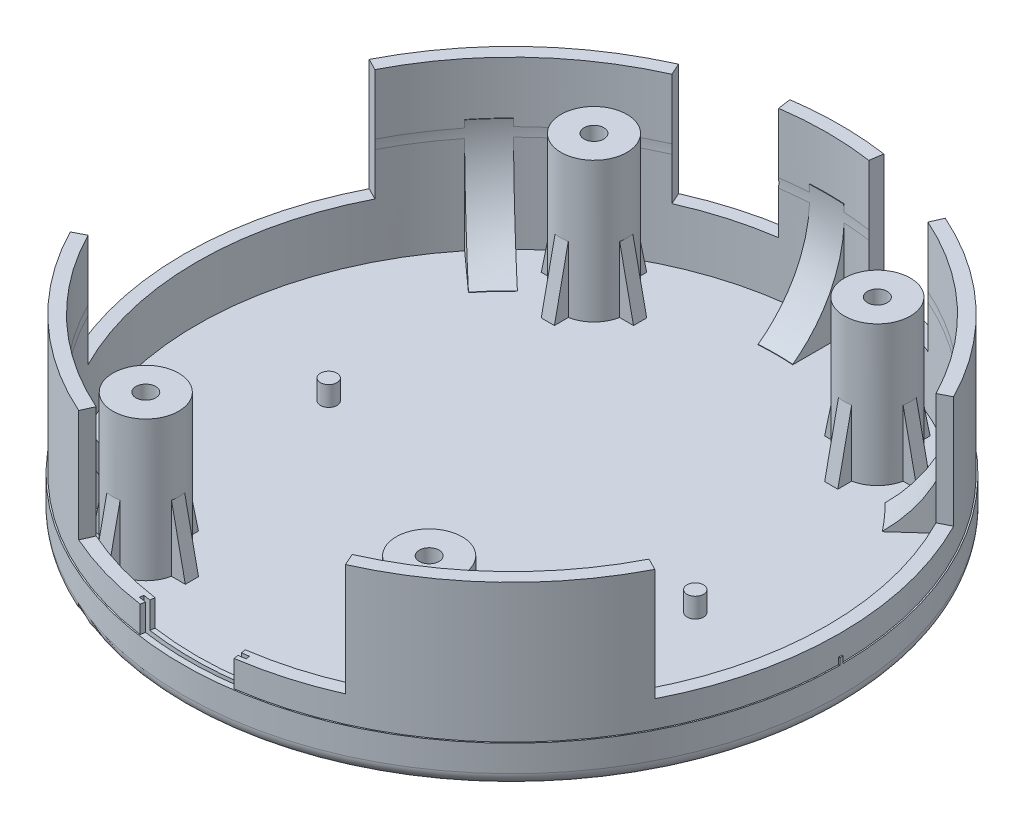
SolidWorks part; units mm, degrees
ref_plane "Front Plane" through (0, 0, 0) normal (0, 0, 1) x (1, 0, 0)
ref_plane "Top Plane" through (0, 0, 0) normal (0, 1, 0) x (1, 0, 0)
ref_plane "Right Plane" through (0, 0, 0) normal (1, 0, 0) x (0, 0, -1)
sketch "Эскиз1" plane through (0, 0, 0) normal (0, 1, 0) x (1, 0, 0)
  circle A0 centre (0, 0) radius 50
  dimension "D1" = 100
extrude "Бобышка-Вытянуть1" add sketch "Эскиз1" along normal blind 6
shell "Оболочка1" thickness 2
sketch "Эскиз3" plane through (0, 2, 0) normal (0, 1, 0) x (1, 0, 0)
  circle A0 centre (0, 0) radius 48 construction
  circle A1 centre (0, 0) radius 48
extrude "Бобышка-Вытянуть2" add sketch "Эскиз3" along normal blind 2
fillet "Скругление1" radius 2 1 edges at (0, 0, 50)
sketch "Эскиз4" plane through (0, 4, 0) normal (0, 1, 0) x (1, 0, 0)
  circle A2 centre (0, 0) radius 47.8
  circle A3 centre (0, 0) radius 49.8
  dimension "D1" = 99.6
  dimension "D2" = 95.6
extrude "Бобышка-Вытянуть3" add sketch "Эскиз4" along normal blind 23
sketch "Эскиз15" plane through (0, 4, 0) normal (0, 1, 0) x (1, 0, 0)
  circle A0 centre (0, 0) radius 50
  circle A1 centre (0, 0) radius 48
  dimension "D1" = 96
  dimension "D2" = 100
extrude "Бобышка-Вытянуть9" add sketch "Эскиз15" along normal blind 2
sketch "Эскиз16" plane through (0, 4, 0) normal (0, 1, 0) x (1, 0, 0)
  line L0 (-37.2524, 30.063) -> (-31.4039, 24.7971)
  line L1 (0, 47.8) -> (2.6705, 47.8) construction
  line L2 (0, 47.8) -> (-2.5855, 47.8) construction
  line L14 (-2.5855, 47.8) -> (-2.5855, 39.9302)
  line L15 (-33.7354, 33.969) -> (-27.8829, 28.6993)
  line L24 (0, 47.8) -> (2.6705, 47.8) construction
  line L25 (2.6705, 47.8) -> (2.6705, 39.9246)
  line L33 (0, 47.8) -> (-2.5855, 47.8) construction
  line L34 (0, 0) -> (0, 14.9931) construction
  line L37 (0, 0) -> (22.7819, 0) construction
  line L38 (0, -47.8) -> (-2.5855, -47.8) construction
  line L41 (33.7354, 33.969) -> (27.8829, 28.6993)
  line L42 (37.2524, 30.063) -> (31.4039, 24.7971)
  line L43 (0, -47.8) -> (2.6705, -47.8) construction
  line L44 (0, -47.8) -> (-2.5855, -47.8) construction
  line L45 (0, -47.8) -> (2.6705, -47.8) construction
  line L46 (37.2524, -30.063) -> (31.4039, -24.7971)
  line L47 (33.7354, -33.969) -> (27.8829, -28.6993)
  line L48 (2.6705, -47.8) -> (2.6705, -39.9246)
  line L49 (-33.7354, -33.969) -> (-27.8829, -28.6993)
  line L50 (-2.5855, -47.8) -> (-2.5855, -39.9302)
  line L51 (-37.2524, -30.063) -> (-31.4039, -24.7971)
  circle A18 centre (0, 0) radius 47.8 construction
  arc A19 (-33.68, 33.919) -> (-37.2004, 30.0162) centre (0, 0) ccw
  arc A20 (-27.8829, 28.6993) -> (-31.4039, 24.7971) centre (0, 0) ccw
  arc A21 (2.6705, 47.7253) -> (-2.5855, 47.73) centre (0, 0) ccw
  arc A22 (2.6705, 39.9246) -> (-2.5855, 39.9302) centre (0, 0) ccw
  arc A23 (33.68, -33.919) -> (37.2004, -30.0162) centre (0, 0) ccw
  arc A24 (27.8829, -28.6993) -> (31.4039, -24.7971) centre (0, 0) ccw
  arc A25 (2.6705, -39.9246) -> (-2.5855, -39.9302) centre (0, 0) cw
  arc A26 (2.6705, -47.7253) -> (-2.5855, -47.73) centre (0, 0) cw
  arc A27 (-27.8829, -28.6993) -> (-31.4039, -24.7971) centre (0, 0) cw
  arc A28 (-33.68, -33.919) -> (-37.2004, -30.0162) centre (0, 0) cw
  arc A29 (27.8829, 28.6993) -> (31.4039, 24.7971) centre (0, 0) cw
  arc A30 (33.68, 33.919) -> (37.2004, 30.0162) centre (0, 0) cw
extrude "Бобышка-Вытянуть10" add sketch "Эскиз16" along normal blind 15
sketch "Эскиз27" plane through (0, 6, 0) normal (0, 1, 0) x (1, 0, 0)
  line L0 (0, 0) -> (-65.748, 0) construction
  line L1 (0, 0) -> (0, 13.4164) construction
  line L14 (49.9994, -0.2541) -> (49.7994, -0.2541)
  line L17 (49.9994, 0.2541) -> (49.7994, 0.2541)
  line L18 (-49.9994, 0.2541) -> (-49.7994, 0.2541)
  line L19 (-49.9994, -0.2541) -> (-49.7994, -0.2541)
  arc A0 (-49.9994, 0.2541) -> (-49.9994, -0.2541) centre (0, 0) ccw
  arc A2 (-49.7994, 0.2541) -> (-49.7994, -0.2541) centre (0, 0) ccw
  arc A13 (49.7994, 0.2541) -> (49.7994, -0.2541) centre (0, 0) cw
  arc A14 (49.9994, 0.2541) -> (49.9994, -0.2541) centre (0, 0) cw
extrude "Бобышка-Вытянуть14" add sketch "Эскиз27" along normal blind 1
sketch "Эскиз28" plane through (0, 4, 0) normal (0, 1, 0) x (1, 0, 0)
  line L0 (-37.2004, 30.0162) -> (-31.4039, 24.7971) construction
  line L2 (-37.2004, 30.0162) -> (-31.4039, 24.7971)
  line L5 (-33.68, 33.919) -> (-27.8829, 28.6993) construction
  line L7 (-33.68, 33.919) -> (-27.8829, 28.6993)
  line L9 (-2.5855, 47.73) -> (-2.5855, 39.9302) construction
  line L11 (-2.5855, 47.73) -> (-2.5855, 39.9302)
  line L14 (2.6705, 47.7253) -> (2.6705, 39.9246) construction
  line L16 (2.6705, 47.7253) -> (2.6705, 39.9246)
  line L19 (33.68, 33.919) -> (27.8829, 28.6993) construction
  line L21 (33.68, 33.919) -> (27.8829, 28.6993)
  line L28 (37.2004, 30.0162) -> (31.4039, 24.7971) construction
  line L30 (37.2004, 30.0162) -> (31.4039, 24.7971)
  line L38 (37.2004, -30.0162) -> (31.4039, -24.7971) construction
  line L39 (37.2004, -30.0162) -> (31.4039, -24.7971)
  line L40 (33.68, -33.919) -> (27.8829, -28.6993) construction
  line L41 (33.68, -33.919) -> (27.8829, -28.6993)
  line L42 (2.6705, -47.7253) -> (2.6705, -39.9246) construction
  line L43 (2.6705, -47.7253) -> (2.6705, -39.9246)
  line L44 (-2.5855, -47.73) -> (-2.5855, -39.9302) construction
  line L45 (-2.5855, -47.73) -> (-2.5855, -39.9302)
  line L46 (-33.68, -33.919) -> (-27.8829, -28.6993) construction
  line L47 (-33.68, -33.919) -> (-27.8829, -28.6993)
  line L48 (-37.2004, -30.0162) -> (-31.4039, -24.7971) construction
  line L49 (-37.2004, -30.0162) -> (-31.4039, -24.7971)
  arc A0 (-37.2004, 30.0162) -> (-37.2004, -30.0162) centre (0, 0) ccw construction
  arc A2 (-37.2004, 30.0162) -> (-37.2004, -30.0162) centre (0, 0) ccw
  arc A4 (-27.8829, 28.6993) -> (-31.4039, 24.7971) centre (0, 0) ccw construction
  arc A6 (-27.8829, 28.6993) -> (-31.4039, 24.7971) centre (0, 0) ccw
  arc A8 (-2.5855, 47.73) -> (-33.68, 33.919) centre (0, 0) ccw construction
  arc A10 (-2.5855, 47.73) -> (-33.68, 33.919) centre (0, 0) ccw
  arc A14 (2.6705, 39.9246) -> (-2.5855, 39.9302) centre (0, 0) ccw construction
  arc A16 (2.6705, 39.9246) -> (-2.5855, 39.9302) centre (0, 0) ccw
  arc A17 (33.68, 33.919) -> (2.6705, 47.7253) centre (0, 0) ccw construction
  arc A18 (33.68, 33.919) -> (2.6705, 47.7253) centre (0, 0) ccw
  arc A19 (31.4039, 24.7971) -> (27.8829, 28.6993) centre (0, 0) ccw construction
  arc A20 (31.4039, 24.7971) -> (27.8829, 28.6993) centre (0, 0) ccw
  arc A21 (37.2004, -30.0162) -> (37.2004, 30.0162) centre (0, 0) ccw construction
  arc A22 (37.2004, -30.0162) -> (37.2004, 30.0162) centre (0, 0) ccw
  arc A23 (27.8829, -28.6993) -> (31.4039, -24.7971) centre (0, 0) ccw construction
  arc A24 (27.8829, -28.6993) -> (31.4039, -24.7971) centre (0, 0) ccw
  arc A25 (2.6705, -47.7253) -> (33.68, -33.919) centre (0, 0) ccw construction
  arc A26 (2.6705, -47.7253) -> (33.68, -33.919) centre (0, 0) ccw
  arc A27 (-2.5855, -39.9302) -> (2.6705, -39.9246) centre (0, 0) ccw construction
  arc A28 (-2.5855, -39.9302) -> (2.6705, -39.9246) centre (0, 0) ccw
  arc A29 (-33.68, -33.919) -> (-2.5855, -47.73) centre (0, 0) ccw construction
  arc A30 (-33.68, -33.919) -> (-2.5855, -47.73) centre (0, 0) ccw
  arc A31 (-31.4039, -24.7971) -> (-27.8829, -28.6993) centre (0, 0) ccw construction
  arc A32 (-31.4039, -24.7971) -> (-27.8829, -28.6993) centre (0, 0) ccw
extrude "Вырез-Вытянуть11" cut sketch "Эскиз28" against normal blind 2.2538
sketch "Эскиз34" plane through (0, 27, 0) normal (0, 1, 0) x (1, 0, 0)
  line L1 (-6.8438, 47.3075) -> (-7.1302, 49.2869)
  line L2 (6.8438, 47.3075) -> (7.1302, 49.2869)
  line L7 (6.8438, -47.3075) -> (7.1302, -49.2869)
  line L8 (-6.8438, -47.3075) -> (-7.1302, -49.2869)
  line L13 (0, 24.6435) -> (0, -23.1565) construction
  line L20 (-0.0643, -46.931) -> (-0.0643, -36.9011) construction
  line L23 (-19.4216, -43.6765) -> (-20.2342, -45.504)
  line L24 (19.4216, -43.6765) -> (20.2342, -45.504)
  line L25 (19.4216, 43.6765) -> (20.2342, 45.504)
  line L26 (-19.4216, 43.6765) -> (-20.2342, 45.504)
  line L27 (-42.5581, 21.7634) -> (-44.3388, 22.674)
  line L28 (-42.5581, -21.7634) -> (-44.3388, -22.674)
  line L29 (42.5581, -21.7634) -> (44.3388, -22.674)
  line L30 (42.5581, 21.7634) -> (44.3388, 22.674)
  circle A44 centre (0, 0) radius 47.8 construction
  arc A45 (-6.8438, 47.3075) -> (-19.4216, 43.6765) centre (0, 0) ccw
  circle A46 centre (0, 0) radius 49.8 construction
  arc A47 (-7.1302, 49.2869) -> (-20.2342, 45.504) centre (0, 0) ccw
  arc A48 (-44.3388, 22.674) -> (-44.3388, -22.674) centre (0, 0) ccw
  arc A49 (-42.5581, 21.7634) -> (-42.5581, -21.7634) centre (0, 0) ccw
  arc A50 (20.2342, 45.504) -> (7.1302, 49.2869) centre (0, 0) ccw
  arc A51 (19.4216, 43.6765) -> (6.8438, 47.3075) centre (0, 0) ccw
  arc A52 (42.5581, -21.7634) -> (42.5581, 21.7634) centre (0, 0) ccw
  arc A53 (44.3388, -22.674) -> (44.3388, 22.674) centre (0, 0) ccw
  arc A54 (6.8438, -47.3075) -> (19.4216, -43.6765) centre (0, 0) ccw
  arc A55 (7.1302, -49.2869) -> (20.2342, -45.504) centre (0, 0) ccw
  arc A56 (-19.4216, -43.6765) -> (-6.8438, -47.3075) centre (0, 0) ccw
  arc A57 (-20.2342, -45.504) -> (-7.1302, -49.2869) centre (0, 0) ccw
extrude "Вырез-Вытянуть12" cut sketch "Эскиз34" against normal blind 17
sketch "Эскиз35" plane through (0, 27, 0) normal (0, 1, 0) x (1, 0, 0)
  line L0 (-7.1302, -49.2869) -> (-7.6647, -52.9814)
  line L2 (0, 0) -> (0, -36.1695) construction
  line L4 (0, 0) -> (21.0035, 0) construction
  line L6 (-6.8438, -47.3075) -> (-7.1302, -49.2869)
  line L9 (6.8438, -47.3075) -> (7.1302, -49.2869)
  line L10 (7.1302, -49.2869) -> (7.6647, -52.9814)
  line L11 (-7.6647, -52.9814) -> (7.6647, -52.9814)
  arc A0 (7.1302, 49.2869) -> (-7.1302, 49.2869) centre (0, 0) ccw construction
  arc A2 (6.8438, 47.3075) -> (-6.8438, 47.3075) centre (0, 0) ccw construction
  arc A3 (-2.5855, -47.73) -> (2.6705, -47.7253) centre (0, 0) ccw construction
  arc A4 (-2.5855, -47.73) -> (2.6705, -47.7253) centre (0, 0) ccw
  arc A5 (-33.68, -33.919) -> (-2.5855, -47.73) centre (0, 0) ccw construction
  arc A6 (-6.8438, -47.3075) -> (-2.5855, -47.73) centre (0, 0) ccw
  arc A7 (2.6705, -47.7253) -> (33.68, -33.919) centre (0, 0) ccw construction
  arc A8 (2.6705, -47.7253) -> (6.8438, -47.3075) centre (0, 0) ccw
extrude "Вырез-Вытянуть13" cut sketch "Эскиз35" against normal blind 21
sketch "Эскиз45" plane through (0, 0, 0) normal (1, 0, 0) x (0, 0, -1)
  line L1 (-47.7253, 19) -> (-39.9246, 19)
  line L3 (-39.9246, 19) -> (-39.9246, 1.7462)
  line L4 (0, 0) -> (0, 15.2612) construction
  arc A0 (-47.7253, 19) -> (-39.9246, 1.7462) centre (-28.767, 17.1811) ccw
revolve "Вырез-Повернуть4" cut sketch "Эскиз45" angle 360 about L4
sketch "Эскиз47" plane through (0, 1.7462, 0) normal (0, 1, 0) x (1, 0, 0)
  line L0 (-0.0643, -46.931) -> (-0.0643, -36.9011) construction
  line L1 (0, 0) -> (7.0344, 0) construction
  line L2 (0, 0) -> (0, -4.9516) construction
  circle A0 centre (21.4357, 34) radius 5
  circle A1 centre (-21.5643, 34) radius 5
  circle A2 centre (-21.5643, -34) radius 5
  circle A3 centre (21.4357, -34) radius 5
  point P13 (-21.5643, 34)
  point P14 (0, 0)
extrude "Бобышка-Вытянуть18" add sketch "Эскиз47" along normal blind 21.25
sketch "Эскиз48" plane through (0, 22.9962, 0) normal (0, 1, 0) x (1, 0, 0)
  circle A0 centre (-21.5643, 34) radius 1.5
  circle A1 centre (21.4357, 34) radius 1.5
  circle A2 centre (21.4357, -34) radius 1.5
  circle A3 centre (-21.5643, -34) radius 1.5
  point P8 (-21.5643, 34)
  point P9 (21.4357, 34)
  point P10 (21.4357, -34)
  point P11 (-21.5643, -34)
  point P12 (21.4357, 34)
  point P13 (21.4357, 34)
extrude "Вырез-Вытянуть20" cut sketch "Эскиз48" against normal up to surface (22.9962 mm away) up to face at (0, 0, 48)
sketch "Эскиз50" plane through (0, 0, 0) normal (0, -1, 0) x (1, 0, 0)
  circle A0 centre (-21.5643, 34) radius 3.1
  circle A1 centre (21.4357, 34) radius 3.1
  circle A2 centre (21.4357, -34) radius 3.1
  circle A3 centre (-21.5643, -34) radius 3.1
  point P8 (21.4357, 34)
extrude "Вырез-Вытянуть21" cut sketch "Эскиз50" against normal blind 19
sketch "Эскиз51" plane through (0, 0, 0) normal (0, -1, 0) x (1, 0, 0)
  line L0 (0, 0) -> (0, 20) construction
  line L1 (-10, 35) -> (10, 35)
  line L2 (-10, 35) -> (-10, 20)
  line L3 (-10, 20) -> (10, 20)
  line L4 (10, 35) -> (10, 20)
  line L5 (-10, 35) -> (10, 20) construction
  line L6 (-10, 20) -> (10, 35) construction
  point P0 (0, 27.5)
  dimension "D1" = 20
  dimension "D2" = 15
extrude "Вырез-Вытянуть22" cut sketch "Эскиз51" against normal blind 0.1
sketch "Эскиз52" plane through (0, 1.7462, 0) normal (0, 1, 0) x (1, 0, 0)
  line L0 (0, 0) -> (27.81, 0) construction
  line L1 (-27.81, 0) -> (0, 0) construction
  circle A0 centre (-27.81, 0) radius 1.25
  circle A1 centre (27.81, 0) radius 1.25
extrude "Бобышка-Вытянуть19" add sketch "Эскиз52" along normal blind 3
sketch "Эскиз53" plane through (0, 1.7462, 0) normal (0, 1, 0) x (1, 0, 0)
  line L0 (-2.5855, -47.73) -> (-2.5855, -39.9302) construction
  line L1 (-2.5855, -47.73) -> (-2.5855, -39.9302)
  line L2 (2.6705, -39.9246) -> (2.6705, -47.7253) construction
  line L3 (2.6705, -39.9246) -> (2.6705, -47.7253)
  line L4 (-2.5855, -39.9302) -> (2.6705, -39.9246)
  arc A0 (-2.5855, -47.73) -> (2.6705, -47.7253) centre (0, 0) ccw construction
  arc A1 (-2.5855, -47.73) -> (2.6705, -47.7253) centre (0, 0) ccw
extrude "Вырез-Вытянуть23" cut sketch "Эскиз53" along normal blind 20
sketch "Эскиз54" plane through (0, 1.7462, 0) normal (0, 1, 0) x (1, 0, 0)
  line L0 (-21.5643, 34) -> (-21.5643, 29) construction
  line L1 (-21.5643, 29) -> (-20.5643, 29) construction
  line L2 (-21.5643, 29) -> (-22.5643, 29) construction
  line L3 (-22.5643, 29) -> (-22.5643, 27)
  line L4 (-20.5643, 29) -> (-20.5643, 27)
  line L5 (-20.5643, 27) -> (-22.5643, 27)
  line L6 (-22.5643, 29) -> (-22.5643, 29.101)
  line L7 (-20.5643, 29) -> (-20.5643, 29.101)
  line L8 (-26.5643, 35) -> (-28.5643, 35)
  line L9 (-26.5643, 33) -> (-28.5643, 33)
  line L10 (-28.5643, 33) -> (-28.5643, 35)
  line L11 (-26.5643, 35) -> (-26.4633, 35)
  line L12 (-26.5643, 33) -> (-26.4633, 33)
  line L13 (-26.5643, 34) -> (-26.5643, 33) construction
  line L14 (-26.5643, 34) -> (-26.5643, 35) construction
  line L15 (-20.5643, 39) -> (-20.5643, 41)
  line L16 (-22.5643, 39) -> (-22.5643, 41)
  line L17 (-22.5643, 41) -> (-20.5643, 41)
  line L18 (-20.5643, 39) -> (-20.5643, 38.899)
  line L19 (-22.5643, 39) -> (-22.5643, 38.899)
  line L20 (-21.5643, 39) -> (-22.5643, 39) construction
  line L21 (-21.5643, 39) -> (-20.5643, 39) construction
  line L22 (-16.5643, 33) -> (-14.5643, 33)
  line L23 (-16.5643, 35) -> (-14.5643, 35)
  line L24 (-14.5643, 35) -> (-14.5643, 33)
  line L25 (-16.5643, 33) -> (-16.6653, 33)
  line L26 (-16.5643, 35) -> (-16.6653, 35)
  line L27 (-16.5643, 34) -> (-16.5643, 35) construction
  line L28 (-16.5643, 34) -> (-16.5643, 33) construction
  line L29 (26.4357, 35) -> (26.3347, 35)
  line L30 (16.4357, 35) -> (16.5367, 35)
  line L31 (16.4357, 33) -> (16.5367, 33)
  line L32 (26.4357, 35) -> (28.4357, 35)
  line L33 (22.4357, 27) -> (20.4357, 27)
  line L34 (20.4357, 41) -> (22.4357, 41)
  line L35 (16.4357, 34) -> (16.4357, 33) construction
  line L36 (20.4357, 29) -> (20.4357, 27)
  line L37 (20.4357, 29) -> (20.4357, 29.101)
  line L38 (20.4357, 39) -> (20.4357, 38.899)
  line L39 (26.4357, 33) -> (26.3347, 33)
  line L40 (22.4357, 39) -> (22.4357, 41)
  line L41 (16.4357, 34) -> (16.4357, 35) construction
  line L42 (14.4357, 33) -> (14.4357, 35)
  line L43 (28.4357, 35) -> (28.4357, 33)
  line L44 (21.4357, 34) -> (21.4357, 29) construction
  line L45 (22.4357, 29) -> (22.4357, 27)
  line L46 (22.4357, 29) -> (22.4357, 29.101)
  line L47 (20.4357, 39) -> (20.4357, 41)
  line L48 (21.4357, 39) -> (22.4357, 39) construction
  line L49 (21.4357, 29) -> (22.4357, 29) construction
  line L50 (21.4357, 39) -> (20.4357, 39) construction
  line L51 (16.4357, 33) -> (14.4357, 33)
  line L52 (22.4357, 39) -> (22.4357, 38.899)
  line L53 (26.4357, 33) -> (28.4357, 33)
  line L54 (16.4357, 35) -> (14.4357, 35)
  line L55 (21.4357, 29) -> (20.4357, 29) construction
  line L56 (26.4357, 34) -> (26.4357, 35) construction
  line L57 (26.4357, 34) -> (26.4357, 33) construction
  line L58 (-20.5643, -29) -> (-20.5643, -27)
  line L59 (20.4357, -39) -> (20.4357, -38.899)
  line L60 (21.4357, -29) -> (20.4357, -29) construction
  line L61 (-22.5643, -39) -> (-22.5643, -38.899)
  line L62 (-16.5643, -35) -> (-14.5643, -35)
  line L63 (16.4357, -35) -> (14.4357, -35)
  line L64 (26.4357, -35) -> (26.3347, -35)
  line L65 (-16.5643, -34) -> (-16.5643, -33) construction
  line L66 (-28.5643, -35) -> (-28.5643, -33)
  line L67 (-22.5643, -29) -> (-22.5643, -27)
  line L68 (26.4357, -33) -> (28.4357, -33)
  line L69 (22.4357, -29) -> (22.4357, -29.101)
  line L70 (22.4357, -41) -> (20.4357, -41)
  line L71 (-21.5643, -29) -> (-22.5643, -29) construction
  line L72 (21.4357, -39) -> (20.4357, -39) construction
  line L73 (20.4357, -39) -> (20.4357, -41)
  line L74 (-21.5643, -29) -> (-20.5643, -29) construction
  line L75 (16.4357, -34) -> (16.4357, -33) construction
  line L76 (26.4357, -34) -> (26.4357, -33) construction
  line L77 (-26.5643, -33) -> (-28.5643, -33)
  line L78 (-26.5643, -33) -> (-26.4633, -33)
  line L79 (-16.5643, -33) -> (-14.5643, -33)
  line L80 (28.4357, -33) -> (28.4357, -35)
  line L81 (26.4357, -35) -> (28.4357, -35)
  line L82 (-22.5643, -39) -> (-22.5643, -41)
  line L83 (21.4357, -39) -> (22.4357, -39) construction
  line L84 (-22.5643, -29) -> (-22.5643, -29.101)
  line L85 (22.4357, -39) -> (22.4357, -38.899)
  line L86 (16.4357, -33) -> (14.4357, -33)
  line L87 (16.4357, -34) -> (16.4357, -35) construction
  line L88 (-16.5643, -34) -> (-16.5643, -35) construction
  line L89 (-26.5643, -35) -> (-28.5643, -35)
  line L90 (-22.5643, -27) -> (-20.5643, -27)
  line L91 (-16.5643, -35) -> (-16.6653, -35)
  line L92 (16.4357, -33) -> (16.5367, -33)
  line L93 (-20.5643, -39) -> (-20.5643, -38.899)
  line L94 (-14.5643, -33) -> (-14.5643, -35)
  line L95 (-16.5643, -33) -> (-16.6653, -33)
  line L96 (-26.5643, -34) -> (-26.5643, -35) construction
  line L97 (-20.5643, -41) -> (-22.5643, -41)
  line L98 (26.4357, -34) -> (26.4357, -35) construction
  line L99 (16.4357, -35) -> (16.5367, -35)
  line L100 (14.4357, -35) -> (14.4357, -33)
  line L101 (20.4357, -29) -> (20.4357, -27)
  line L102 (-21.5643, -39) -> (-22.5643, -39) construction
  line L103 (21.4357, -34) -> (21.4357, -39) construction
  line L104 (-20.5643, -39) -> (-20.5643, -41)
  line L105 (26.4357, -33) -> (26.3347, -33)
  line L106 (20.4357, -29) -> (20.4357, -29.101)
  line L107 (22.4357, -39) -> (22.4357, -41)
  line L108 (-21.5643, -34) -> (-21.5643, -39) construction
  line L109 (-20.5643, -29) -> (-20.5643, -29.101)
  line L110 (22.4357, -29) -> (22.4357, -27)
  line L111 (-26.5643, -35) -> (-26.4633, -35)
  line L112 (20.4357, -27) -> (22.4357, -27)
  line L113 (-21.5643, -39) -> (-20.5643, -39) construction
  line L114 (-26.5643, -34) -> (-26.5643, -33) construction
  line L115 (21.4357, -29) -> (22.4357, -29) construction
  circle A0 centre (-21.5643, 34) radius 5 construction
  arc A1 (-22.5643, 29.101) -> (-20.5643, 29.101) centre (-21.5643, 34) ccw
  arc A2 (-26.4633, 35) -> (-26.4633, 33) centre (-21.5643, 34) ccw
  arc A3 (-20.5643, 38.899) -> (-22.5643, 38.899) centre (-21.5643, 34) ccw
  arc A4 (-16.6653, 33) -> (-16.6653, 35) centre (-21.5643, 34) ccw
  arc A5 (22.4357, 38.899) -> (20.4357, 38.899) centre (21.4357, 34) ccw
  arc A6 (26.3347, 33) -> (26.3347, 35) centre (21.4357, 34) ccw
  arc A7 (20.4357, 29.101) -> (22.4357, 29.101) centre (21.4357, 34) ccw
  arc A8 (16.5367, 35) -> (16.5367, 33) centre (21.4357, 34) ccw
  arc A9 (-26.4633, -33) -> (-26.4633, -35) centre (-21.5643, -34) ccw
  arc A10 (22.4357, -29.101) -> (20.4357, -29.101) centre (21.4357, -34) ccw
  arc A11 (-20.5643, -29.101) -> (-22.5643, -29.101) centre (-21.5643, -34) ccw
  arc A12 (26.3347, -35) -> (26.3347, -33) centre (21.4357, -34) ccw
  arc A13 (16.5367, -33) -> (16.5367, -35) centre (21.4357, -34) ccw
  arc A14 (-16.6653, -35) -> (-16.6653, -33) centre (-21.5643, -34) ccw
  arc A15 (-22.5643, -38.899) -> (-20.5643, -38.899) centre (-21.5643, -34) ccw
  arc A16 (20.4357, -38.899) -> (22.4357, -38.899) centre (21.4357, -34) ccw
  point P33 (-21.5643, 34)
  point P60 (21.4357, 34)
  point P93 (-21.5643, -34)
  point P120 (21.4357, -34)
  dimension "D1" = 4
extrude "Бобышка-Вытянуть20" add sketch "Эскиз54" along normal blind 10
sketch "Эскиз55" plane through (-20.5643, 0, 0) normal (1, 0, 0) x (0, 0, -1)
  line L0 (41, 11.7462) -> (41, 1.7462) construction
  line L1 (38.899, 11.7462) -> (41, 11.7462) construction
  line L2 (27, 11.7462) -> (27, 1.7462) construction
  line L3 (27, 11.7462) -> (29.101, 11.7462) construction
  line L4 (-41, 11.7462) -> (-41, 1.7462) construction
  line L5 (-41, 11.7462) -> (-38.899, 11.7462) construction
  line L6 (-27, 11.7462) -> (-27, 1.7462) construction
  line L7 (-29.101, 11.7462) -> (-27, 11.7462) construction
  line L8 (41, 11.7462) -> (41, 1.7462)
  line L9 (38.899, 11.7462) -> (41, 11.7462)
  line L10 (27, 11.7462) -> (27, 1.7462)
  line L11 (27, 11.7462) -> (29.101, 11.7462)
  line L12 (-41, 11.7462) -> (-41, 1.7462)
  line L13 (-41, 11.7462) -> (-38.899, 11.7462)
  line L14 (-27, 11.7462) -> (-27, 1.7462)
  line L15 (-29.101, 11.7462) -> (-27, 11.7462)
  line L16 (29.101, 11.7462) -> (27, 1.7462)
  line L17 (38.899, 11.7462) -> (41, 1.7462)
  line L18 (-29.101, 11.7462) -> (-27, 1.7462)
  line L19 (-38.899, 11.7462) -> (-41, 1.7462)
extrude "Вырез-Вытянуть24" cut sketch "Эскиз55" against normal up to surface (2 mm away) up to face at (-22.5643, 6.7462, 28.0505)
sketch "Эскиз56" plane through (20.4357, 0, 0) normal (-1, 0, 0) x (0, 0, 1)
  line L0 (41, 11.7462) -> (41, 1.7462) construction
  line L1 (38.899, 11.7462) -> (41, 11.7462) construction
  line L2 (27, 11.7462) -> (27, 1.7462) construction
  line L3 (27, 11.7462) -> (29.101, 11.7462) construction
  line L4 (-41, 11.7462) -> (-41, 1.7462) construction
  line L5 (-27, 11.7462) -> (-27, 1.7462) construction
  line L6 (-29.101, 11.7462) -> (-27, 11.7462) construction
  line L7 (-41, 11.7462) -> (-38.899, 11.7462) construction
  line L8 (41, 11.7462) -> (41, 1.7462)
  line L9 (38.899, 11.7462) -> (41, 11.7462)
  line L10 (27, 11.7462) -> (27, 1.7462)
  line L11 (27, 11.7462) -> (29.101, 11.7462)
  line L12 (-41, 11.7462) -> (-41, 1.7462)
  line L13 (-27, 11.7462) -> (-27, 1.7462)
  line L14 (-29.101, 11.7462) -> (-27, 11.7462)
  line L15 (-41, 11.7462) -> (-38.899, 11.7462)
  line L16 (38.899, 11.7462) -> (41, 1.7462)
  line L17 (29.101, 11.7462) -> (27, 1.7462)
  line L18 (-29.101, 11.7462) -> (-27, 1.7462)
  line L19 (-38.899, 11.7462) -> (-41, 1.7462)
extrude "Вырез-Вытянуть25" cut sketch "Эскиз56" against normal up to surface (2 mm away) up to face at (22.4357, 6.7462, -28.0505)
sketch "Эскиз57" plane through (0, 0, -33) normal (0, 0, 1) x (1, 0, 0)
  line L0 (28.4357, 11.7462) -> (28.4357, 1.7462) construction
  line L1 (26.3347, 11.7462) -> (28.4357, 11.7462) construction
  line L2 (14.4357, 11.7462) -> (14.4357, 1.7462) construction
  line L3 (14.4357, 11.7462) -> (16.5367, 11.7462) construction
  line L4 (-28.5643, 11.7462) -> (-28.5643, 1.7462) construction
  line L5 (-28.5643, 11.7462) -> (-26.4633, 11.7462) construction
  line L6 (-14.5643, 11.7462) -> (-14.5643, 1.7462) construction
  line L7 (-16.6653, 11.7462) -> (-14.5643, 11.7462) construction
  line L8 (28.4357, 11.7462) -> (28.4357, 1.7462)
  line L9 (26.3347, 11.7462) -> (28.4357, 11.7462)
  line L10 (14.4357, 11.7462) -> (14.4357, 1.7462)
  line L11 (14.4357, 11.7462) -> (16.5367, 11.7462)
  line L12 (-28.5643, 11.7462) -> (-28.5643, 1.7462)
  line L13 (-28.5643, 11.7462) -> (-26.4633, 11.7462)
  line L14 (-14.5643, 11.7462) -> (-14.5643, 1.7462)
  line L15 (-16.6653, 11.7462) -> (-14.5643, 11.7462)
  line L16 (26.3347, 11.7462) -> (28.4357, 1.7462)
  line L17 (16.5367, 11.7462) -> (14.4357, 1.7462)
  line L18 (-16.6653, 11.7462) -> (-14.5643, 1.7462)
  line L19 (-26.4633, 11.7462) -> (-28.5643, 1.7462)
extrude "Вырез-Вытянуть26" cut sketch "Эскиз57" against normal up to surface (2 mm away) up to face at (-15.6148, 6.7462, -35)
sketch "Эскиз58" plane through (0, 0, 33) normal (0, 0, -1) x (-1, 0, 0)
  line L0 (-28.4357, 11.7462) -> (-28.4357, 1.7462) construction
  line L1 (-28.4357, 11.7462) -> (-26.3347, 11.7462) construction
  line L2 (-14.4357, 11.7462) -> (-14.4357, 1.7462) construction
  line L3 (-16.5367, 11.7462) -> (-14.4357, 11.7462) construction
  line L4 (28.5643, 11.7462) -> (28.5643, 1.7462) construction
  line L5 (26.4633, 11.7462) -> (28.5643, 11.7462) construction
  line L6 (14.5643, 11.7462) -> (14.5643, 1.7462) construction
  line L7 (14.5643, 11.7462) -> (16.6653, 11.7462) construction
  line L8 (-28.4357, 11.7462) -> (-28.4357, 1.7462)
  line L9 (-28.4357, 11.7462) -> (-26.3347, 11.7462)
  line L10 (-14.4357, 11.7462) -> (-14.4357, 1.7462)
  line L11 (-16.5367, 11.7462) -> (-14.4357, 11.7462)
  line L12 (28.5643, 11.7462) -> (28.5643, 1.7462)
  line L13 (26.4633, 11.7462) -> (28.5643, 11.7462)
  line L14 (14.5643, 11.7462) -> (14.5643, 1.7462)
  line L15 (14.5643, 11.7462) -> (16.6653, 11.7462)
  line L16 (-26.3347, 11.7462) -> (-28.4357, 1.7462)
  line L17 (-16.5367, 11.7462) -> (-14.4357, 1.7462)
  line L18 (16.6653, 11.7462) -> (14.5643, 1.7462)
  line L19 (26.4633, 11.7462) -> (28.5643, 1.7462)
extrude "Вырез-Вытянуть27" cut sketch "Эскиз58" against normal up to surface (2 mm away)
sketch "Эскиз59" plane through (0, 10, 0) normal (0, 1, 0) x (1, 0, 0)
  line L2 (-8.0011, -47.8355) -> (-8.1001, -48.4272)
  line L3 (0, 0) -> (0, -9.7538) construction
  line L4 (8.0011, -47.8355) -> (8.1001, -48.4272)
  arc A4 (-8.0011, -47.8355) -> (8.0011, -47.8355) centre (0, 0) ccw
  arc A5 (-8.1001, -48.4272) -> (8.1001, -48.4272) centre (0, 0) ccw
extrude "Вырез-Вытянуть28" cut sketch "Эскиз59" against normal blind 6
